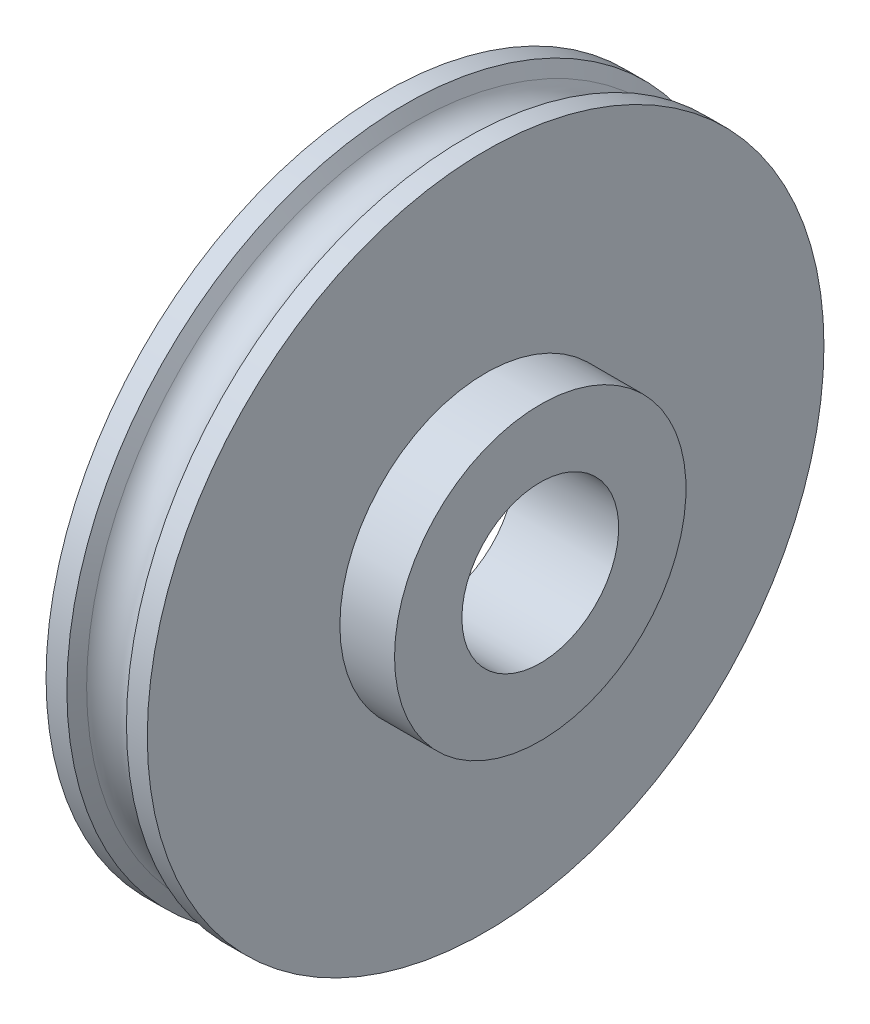
SolidWorks part; units mm, degrees
ref_plane "Front" through (0, 0, 0) normal (0, 0, 1) x (1, 0, 0)
ref_plane "Top" through (0, 0, 0) normal (0, 1, 0) x (1, 0, 0)
ref_plane "Right" through (0, 0, 0) normal (1, 0, 0) x (0, 0, -1)
sketch "Sketch1" plane through (0, 0, 0) normal (0, 0, 1) x (1, 0, 0)
  line L0 (0, 0) -> (2.4227, 0) construction
  line L1 (1, 1.506) -> (1, 4.04)
  line L2 (1, 4.04) -> (0, 4.04)
  line L3 (0, 4.04) -> (0, 6.5)
  line L5 (0.4, 6.5) -> (0.5358, 6.2565)
  line L6 (1.4092, 6.2565) -> (1.545, 6.5)
  line L7 (0, 6.5) -> (1.945, 6.5)
  line L8 (1.945, 6.5) -> (1.945, 2.8)
  line L9 (1.945, 2.8) -> (2.995, 2.8)
  line L10 (2.995, 2.8) -> (2.995, 1.506)
  line L11 (2.995, 1.506) -> (1, 1.506)
  arc A0 (0.5358, 6.2565) -> (1.4092, 6.2565) centre (0.9725, 6.5) ccw
  point P2 (0, 0)
  point P17 (-0.0275, 6.5)
  point P18 (-0.5711, 6.5)
  point P19 (0.5241, 6.5)
  point P20 (0, 6.5)
  dimension "D9" = 0.5
  dimension "D1" = 1
  dimension "D2" = 1.995
  dimension "D3" = 1.945
  dimension "D4" = 1.506
  dimension "D5" = 2.8
  dimension "D6" = 6.5
  dimension "D7" = 4.04
  dimension "D8" = 1.145
revolve "Revolve1" add sketch "Sketch1" angle 360 about L0
